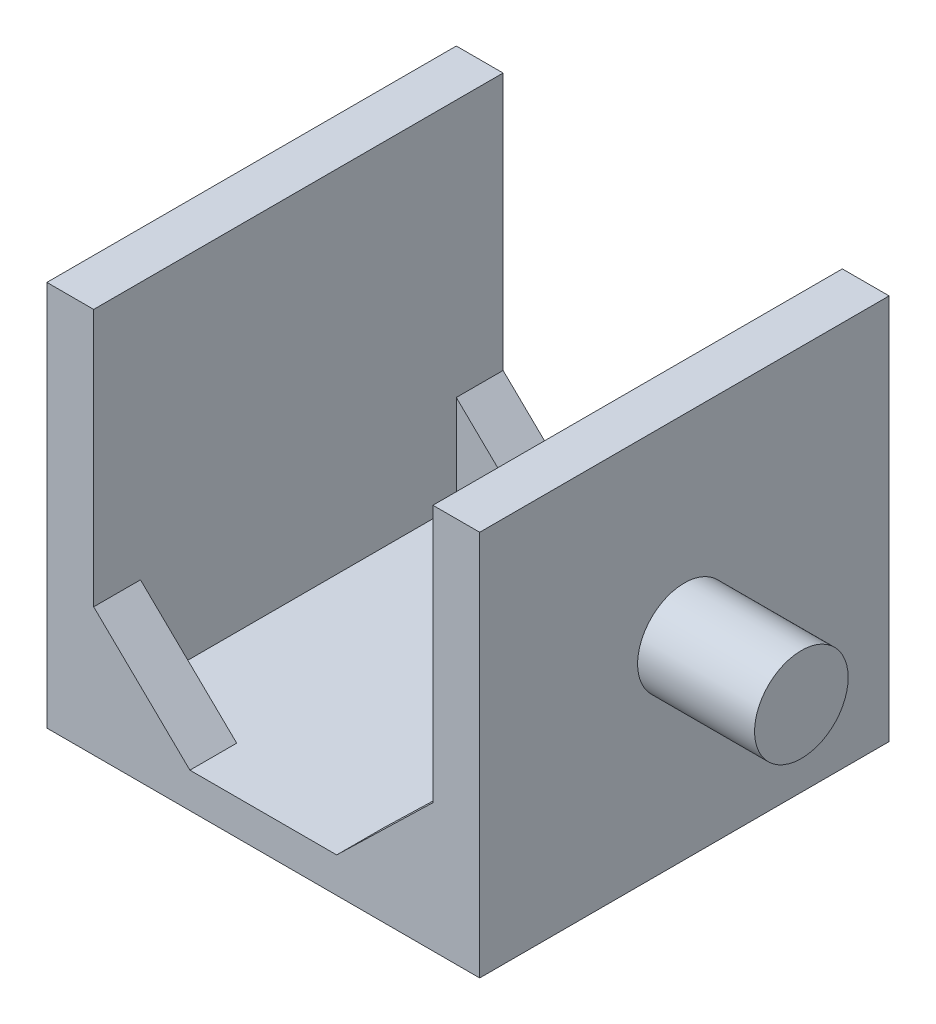
SolidWorks part; units mm, degrees
ref_plane "Front Plane" through (0, 0, 0) normal (0, 0, 1) x (1, 0, 0)
ref_plane "Top Plane" through (0, 0, 0) normal (0, 1, 0) x (1, 0, 0)
ref_plane "Right Plane" through (0, 0, 0) normal (1, 0, 0) x (0, 0, -1)
sketch "Sketch1" plane through (0, 0, 0) normal (0, 1, 0) x (1, 0, 0)
  line L1 (-18.5, -17.5) -> (18.5, -17.5)
  line L2 (-18.5, -17.5) -> (-18.5, 17.5)
  line L3 (-18.5, 17.5) -> (18.5, 17.5)
  line L4 (18.5, -17.5) -> (18.5, 17.5)
  line L5 (-18.5, -17.5) -> (18.5, 17.5) construction
  line L6 (-18.5, 17.5) -> (18.5, -17.5) construction
  circle A0 centre (0, 0) radius 2
  point P0 (0, 0)
  dimension "D3" = 4
  dimension "D1" = 35
  dimension "D2" = 37
extrude "Boss-Extrude1" add sketch "Sketch1" along normal blind 3
sketch "Sketch2" plane through (0, 3, 0) normal (0, 1, 0) x (1, 0, 0)
  line L0 (-18.5, -17.5) -> (18.5, -17.5) construction
  line L1 (-18.5, 17.5) -> (-14.5, 17.5)
  line L2 (-18.5, 17.5) -> (-18.5, -17.5)
  line L3 (-18.5, -17.5) -> (-14.5, -17.5)
  line L4 (-14.5, 17.5) -> (-14.5, -17.5)
  line L6 (18.5, 17.5) -> (14.5, 17.5)
  line L7 (18.5, 17.5) -> (18.5, -17.5)
  line L8 (18.5, -17.5) -> (14.5, -17.5)
  line L9 (14.5, 17.5) -> (14.5, -17.5)
  dimension "D1" = 4
  dimension "D2" = 4
extrude "Boss-Extrude2" add sketch "Sketch2" along normal blind 30
sketch "Sketch3" plane through (-18.5, 0, 0) normal (-1, 0, 0) x (0, 0, 1)
  line L0 (0, 33) -> (0, 0) construction
  line L1 (-17.5, 33) -> (17.5, 33) construction
  circle A0 centre (0, 16.5) radius 4
  dimension "D1" = 8
extrude "Boss-Extrude3" add sketch "Sketch3" along normal blind 8
sketch "Sketch4" plane through (18.5, 0, 0) normal (1, 0, 0) x (0, 0, -1)
  circle A0 centre (0, 16.5) radius 4
  dimension "D1" = 8
extrude "Boss-Extrude4" add sketch "Sketch4" along normal blind 10
sketch "Sketch5" plane through (0, 0, 17.5) normal (0, 0, 1) x (1, 0, 0)
  line L0 (-14.5, 10.9791) -> (-6.2729, 3)
  line L1 (-14.5, 33) -> (-14.5, 3) construction
  line L2 (-14.5, 3) -> (14.5, 3) construction
  line L3 (-6.2729, 3) -> (-14.5, 3)
  line L4 (-14.5, 3) -> (-14.5, 10.9791)
extrude "Boss-Extrude5" add sketch "Sketch5" against normal blind 4
mirror "Mirror1" about plane through (0, 0, 0) normal (1, 0, 0) of "Boss-Extrude5"
mirror "Mirror2" about plane through (0, 0, 0) normal (0, 0, 1) of "Mirror1", "Boss-Extrude5"
